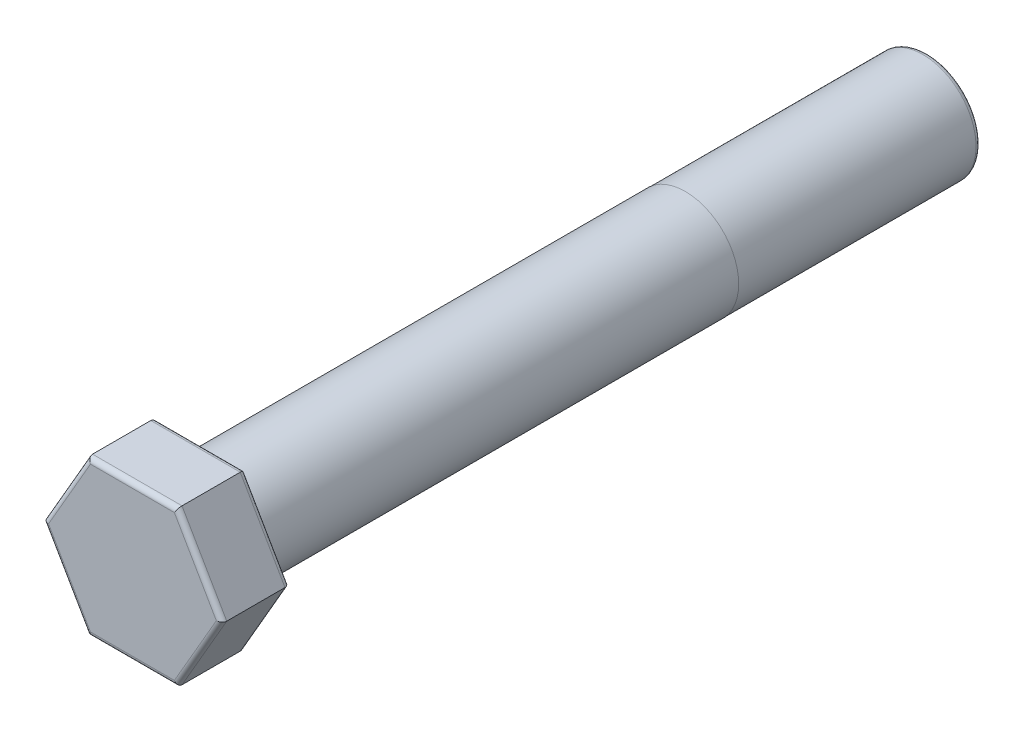
SolidWorks part; units mm, degrees
ref_plane "前视基准面" through (0, 0, 0) normal (0, 0, 1) x (1, 0, 0)
ref_plane "上视基准面" through (0, 0, 0) normal (0, 1, 0) x (1, 0, 0)
ref_plane "右视基准面" through (0, 0, 0) normal (1, 0, 0) x (0, 0, -1)
sketch "草图2" plane through (0, 0, 0) normal (0, 0, 1) x (1, 0, 0)
  line L1 (9.225, -15.9782) -> (18.45, 0)
  line L2 (18.45, 0) -> (9.225, 15.9782)
  line L3 (9.225, 15.9782) -> (-9.225, 15.9782)
  line L4 (-9.225, 15.9782) -> (-18.45, 0)
  line L5 (-18.45, 0) -> (-9.225, -15.9782)
  line L6 (-9.225, -15.9782) -> (9.225, -15.9782)
  circle A0 centre (0, 0) radius 15.9782 construction
  dimension "D1" = 36.9
extrude "拉伸1" add sketch "草图2" along normal blind 14
sketch "草图3" plane through (0, 0, 0) normal (0, 0, -1) x (-1, 0, 0)
  circle A0 centre (0, 0) radius 11
  dimension "D1" = 22
extrude "拉伸2" add sketch "草图3" along normal blind 100
sketch "草图4" plane through (0, 0, -100) normal (0, 0, -1) x (-1, 0, 0)
  circle A0 centre (0, 0) radius 10.95
  circle A1 centre (0, 0) radius 11 construction
  dimension "D1" = 21.9
extrude "拉伸4" add sketch "草图4" along normal blind 50
fillet "圆角2" radius 1 13 edges at (-10.95, 0, -150) (13.8375, 7.9891, 0) (13.8375, -7.9891, 0) (0, -15.9782, 14) (-13.8375, -7.9891, 14) (-13.8375, 7.9891, 14) (0, 15.9782, 14) (13.8375, 7.9891, 14) (13.8375, -7.9891, 14) (0, 15.9782, 0) (-13.8375, 7.9891, 0) (-13.8375, -7.9891, 0) (0, -15.9782, 0)
